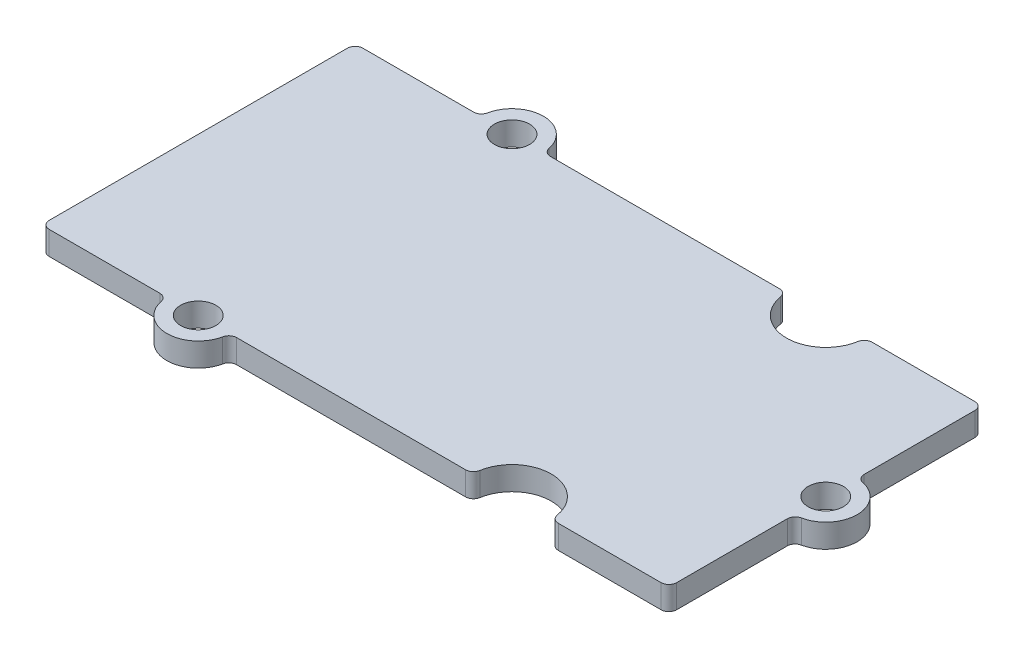
SolidWorks part; units mm, degrees
ref_plane "Front Plane" through (0, 0, 0) normal (0, 0, 1) x (1, 0, 0)
ref_plane "Top Plane" through (0, 0, 0) normal (0, 1, 0) x (1, 0, 0)
ref_plane "Right Plane" through (0, 0, 0) normal (1, 0, 0) x (0, 0, -1)
sketch "Sketch1" plane through (0, 0, 0) normal (0, 1, 0) x (1, 0, 0)
  line L0 (-80.4977, 0) -> (80.4977, 0) construction
  line L1 (-20, -10) -> (20, -10)
  line L2 (-20, -10) -> (-20, 10)
  line L3 (-20, 10) -> (20, 10)
  line L4 (20, -10) -> (20, 10)
  line L5 (-20, -10) -> (20, 10) construction
  line L6 (-20, 10) -> (20, -10) construction
  circle A0 centre (-10, 10) radius 2
  circle A1 centre (-10, -10) radius 2
  circle A2 centre (20, 0) radius 2
  circle A3 centre (10, 10) radius 2.5
  circle A4 centre (10, -10) radius 2.5
  point P0 (0, 0)
  dimension "D3" = 4
  dimension "D5" = 5
  dimension "D6" = 10
  dimension "D1" = 40
  dimension "D2" = 20
  dimension "D4" = 30
extrude "Boss-Extrude1" add sketch "Sketch1" along normal blind 1.5 contours L1 A4 L4 A2 L3 A3 A0 L2 A1
fillet "Fillet1" radius 0.5 14 edges at (7.5, 0.75, -10) (12.5, 0.75, -10) (12.5, 0.75, 10) (7.5, 0.75, 10) (20, 0.75, 2) (20, 0.75, -2) (20, 0.75, -10) (20, 0.75, 10) (-8, 0.75, 10) (-12, 0.75, 10) (-8, 0.75, -10) (-12, 0.75, -10) (-20, 0.75, -10) (-20, 0.75, 10)
sketch "Sketch2" plane through (0, 1.5, 0) normal (0, 1, 0) x (1, 0, 0)
  circle A0 centre (20, 0) radius 1.125
  circle A1 centre (-10, -10) radius 1.125
  circle A2 centre (-10, 10) radius 1.125
  dimension "D1" = 2.25
extrude "Cut-Extrude1" cut sketch "Sketch2" against normal through all
